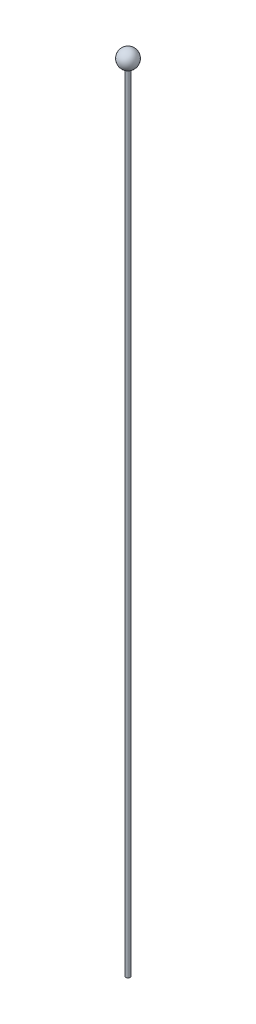
SolidWorks part; units mm, degrees
material "Beech"
ref_plane "Front Plane" through (0, 0, 0) normal (0, 0, 1) x (1, 0, 0)
ref_plane "Top Plane" through (0, 0, 0) normal (0, 1, 0) x (1, 0, 0)
ref_plane "Right Plane" through (0, 0, 0) normal (1, 0, 0) x (0, 0, -1)
sketch "Sketch1" plane through (0, 0, 0) normal (0, 0, 1) x (1, 0, 0)
  line L0 (0, 0) -> (0, 90)
  line L1 (0, 0) -> (0, 331.2662) construction
  line L2 (0, 91) -> (0, 90)
  line L3 (0.25, 89.0318) -> (0.25, 0)
  line L4 (0.25, 0) -> (0, 0)
  arc A0 (0.25, 89.0318) -> (0, 91) centre (0, 90) ccw
  dimension "D2" = 0.5
  dimension "D3" = 2
  dimension "D1" = 90
revolve "Revolve1" add sketch "Sketch1" angle 360 about L1
